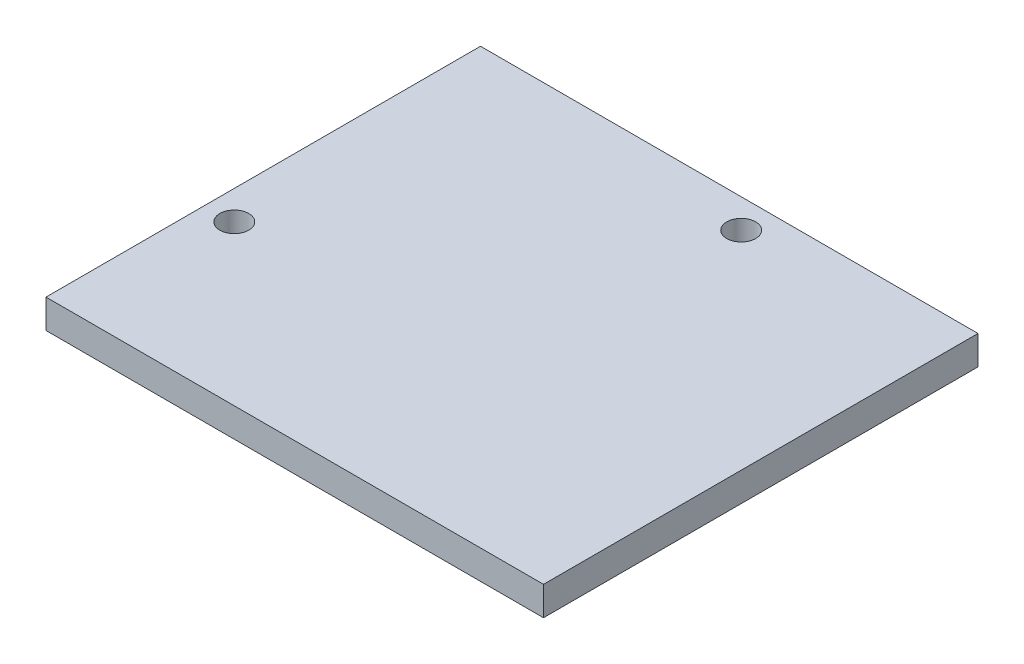
SolidWorks part; units mm, degrees
ref_plane "Front Plane" through (0, 0, 0) normal (0, 0, 1) x (1, 0, 0)
ref_plane "Top Plane" through (0, 0, 0) normal (0, 1, 0) x (1, 0, 0)
ref_plane "Right Plane" through (0, 0, 0) normal (1, 0, 0) x (0, 0, -1)
sketch "Sketch1" plane through (0, 0, 0) normal (0, 1, 0) x (1, 0, 0)
  line L0 (0, -2.54) -> (25.4, -2.54) construction
  line L1 (0, -38.1) -> (43.6245, -38.1)
  line L2 (0, -38.1) -> (0, 0)
  line L3 (0, 0) -> (43.6245, 0)
  line L4 (43.6245, -38.1) -> (43.6245, 0)
  line L5 (2.54, 0) -> (2.54, -24.13) construction
  circle A0 centre (25.4, -2.54) radius 1.27
  circle A1 centre (2.54, -24.13) radius 1.27
  dimension "D3" = 2.54
  dimension "D1" = 43.6245
  dimension "D2" = 38.1
  dimension "D4" = 2.54
  dimension "D5" = 25.4
  dimension "D6" = 2.54
  dimension "D7" = 24.13
extrude "Boss-Extrude1" add sketch "Sketch1" along normal blind 2.54
